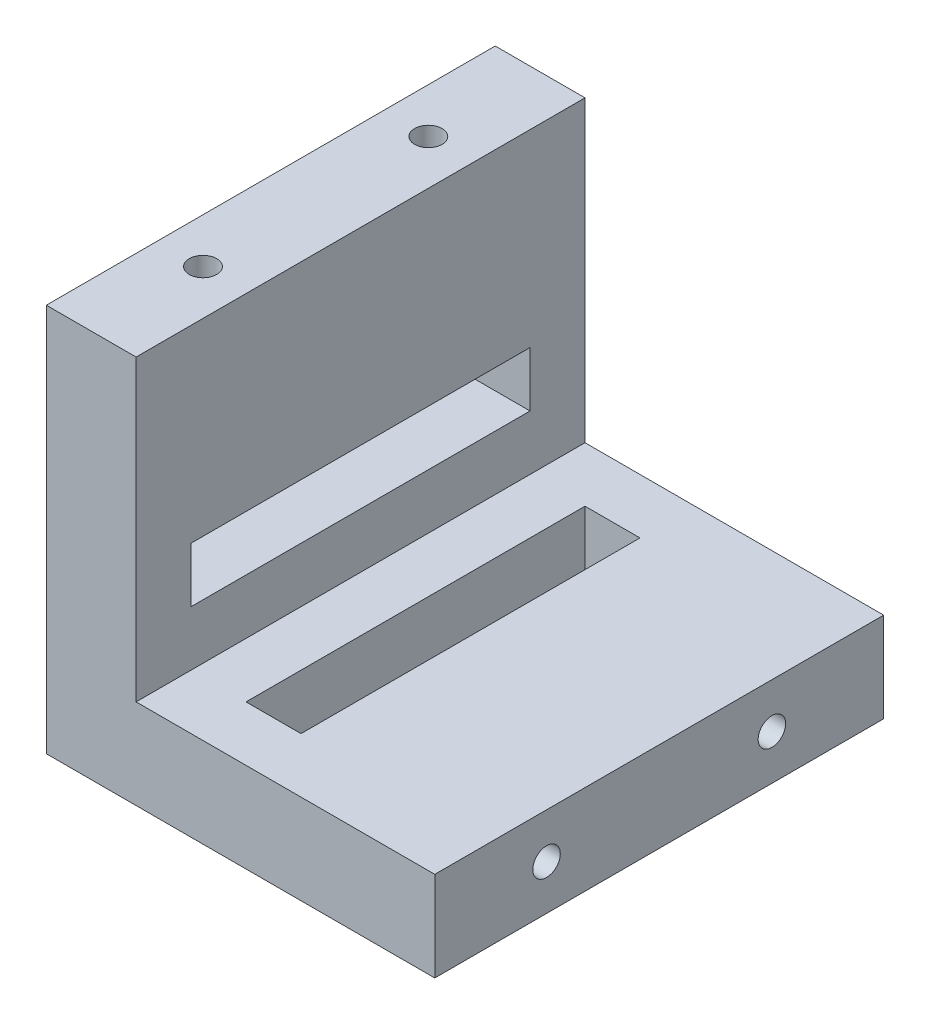
SolidWorks part; units mm, degrees
ref_plane "前基準面" through (0, 0, 0) normal (0, 0, 1) x (1, 0, 0)
ref_plane "上基準面" through (0, 0, 0) normal (0, 1, 0) x (1, 0, 0)
ref_plane "右基準面" through (0, 0, 0) normal (1, 0, 0) x (0, 0, -1)
sketch "草圖1" plane through (0, 0, 0) normal (0, 0, 1) x (1, 0, 0)
  line L0 (0, 0) -> (0, 21.2)
  line L1 (0, 21.2) -> (4.9, 21.2)
  line L2 (4.9, 21.2) -> (4.9, 4.9)
  line L3 (4.9, 4.9) -> (21.2, 4.9)
  line L4 (21.2, 4.9) -> (21.2, 0)
  line L5 (21.2, 0) -> (0, 0)
  dimension "D1" = 16.3
  dimension "D2" = 16.3
  dimension "D3" = 4.9
  dimension "D4" = 4.9
extrude "填料-伸長1" add sketch "草圖1" along normal blind 24.5
sketch "草圖2" plane through (21.2, 0, 0) normal (1, 0, 0) x (0, 0, -1)
  line L0 (0, 2.45) -> (-24.5, 2.45) construction
  line L1 (0, 0) -> (0, 4.9) construction
  line L2 (-24.5, 0) -> (-24.5, 4.9) construction
  circle A0 centre (-6.1, 2.45) radius 0.75
  circle A1 centre (-18.4, 2.45) radius 0.75
  dimension "D1" = 1.5
  dimension "D2" = 1.5
  dimension "D3" = 6.1
  dimension "D4" = 6.1
extrude "除料-伸長1" cut sketch "草圖2" against normal blind 5
sketch "草圖3" plane through (0, 21.2, 0) normal (0, 1, 0) x (1, 0, 0)
  line L0 (2.45, 0) -> (2.45, -24.5) construction
  line L1 (4.9, 0) -> (0, 0) construction
  line L2 (4.9, -24.5) -> (0, -24.5) construction
  circle A0 centre (2.45, -6.1) radius 0.75
  circle A1 centre (2.45, -18.4) radius 0.75
  dimension "D3" = 1.5
  dimension "D4" = 1.5
  dimension "D1" = 6.1
  dimension "D2" = 6.1
extrude "除料-伸長2" cut sketch "草圖3" against normal blind 5
sketch "草圖4" plane through (0, 4.9, 0) normal (0, 1, 0) x (-1, 0, 0)
  line L0 (-21.2, 24.5) -> (-4.9, 24.5) construction
  line L1 (-7.9, 3) -> (-10.9, 3)
  line L2 (-7.9, 3) -> (-7.9, 21.5)
  line L3 (-7.9, 21.5) -> (-10.9, 21.5)
  line L4 (-10.9, 3) -> (-10.9, 21.5)
  line L5 (-7.9, 3) -> (-10.9, 21.5) construction
  line L6 (-7.9, 21.5) -> (-10.9, 3) construction
  line L7 (-21.2, 0) -> (-4.9, 0) construction
  line L8 (-4.9, 24.5) -> (-4.9, 0) construction
  point P0 (-9.4, 12.25)
  dimension "D1" = 3
  dimension "D2" = 3
  dimension "D3" = 3
  dimension "D4" = 6
extrude "除料-伸長3" cut sketch "草圖4" against normal blind 5
sketch "草圖5" plane through (4.9, 0, 0) normal (1, 0, 0) x (0, 0, -1)
  line L0 (0, 4.9) -> (0, 21.2) construction
  line L1 (-3, 10.9) -> (-21.5, 10.9)
  line L2 (-3, 10.9) -> (-3, 7.9)
  line L3 (-3, 7.9) -> (-21.5, 7.9)
  line L4 (-21.5, 10.9) -> (-21.5, 7.9)
  line L5 (-3, 10.9) -> (-21.5, 7.9) construction
  line L6 (-3, 7.9) -> (-21.5, 10.9) construction
  line L7 (-24.5, 4.9) -> (-24.5, 21.2) construction
  line L8 (-24.5, 4.9) -> (0, 4.9) construction
  point P0 (-12.25, 9.4)
  dimension "D1" = 3
  dimension "D2" = 3
  dimension "D3" = 3
  dimension "D4" = 6
extrude "除料-伸長4" cut sketch "草圖5" against normal blind 5
